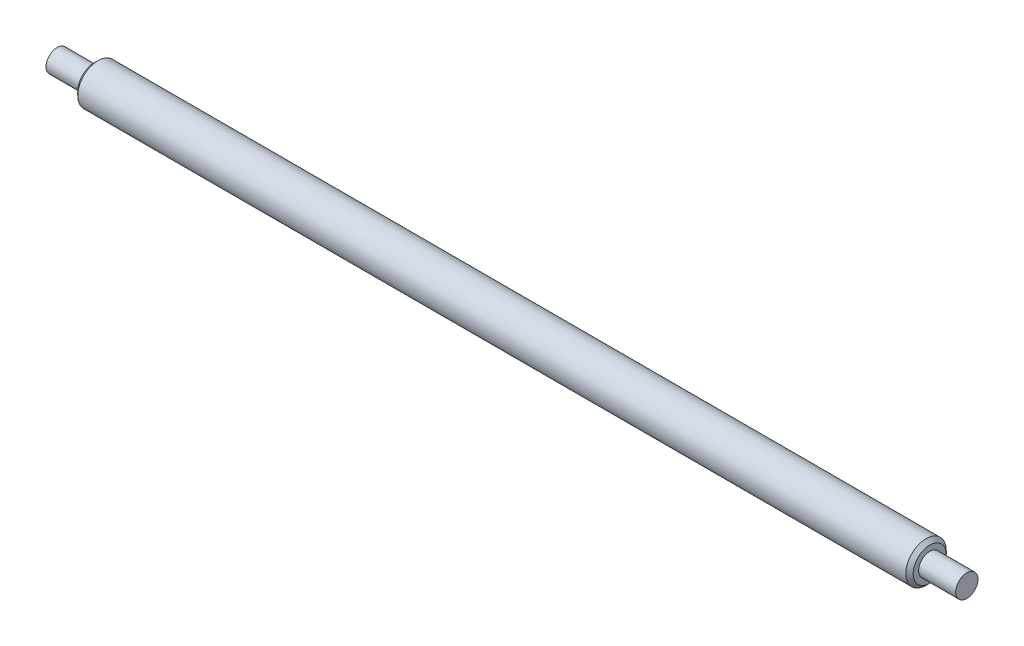
SolidWorks part; units mm, degrees
ref_plane "Front Plane" through (0, 0, 0) normal (0, 0, 1) x (1, 0, 0)
ref_plane "Top Plane" through (0, 0, 0) normal (0, 1, 0) x (1, 0, 0)
ref_plane "Right Plane" through (0, 0, 0) normal (1, 0, 0) x (0, 0, -1)
sketch "Sketch1" plane through (0, 0, 0) normal (1, 0, 0) x (0, 0, -1)
  circle A0 centre (0, 0) radius 10.9
  dimension "D1" = 21.8
extrude "Boss-Extrude1" add sketch "Sketch1" along normal mid plane 490
sketch "Sketch2" plane through (245, 0, 0) normal (1, 0, 0) x (0, 0, -1)
  circle A1 centre (0, 0) radius 6
  circle A2 centre (0, 0) radius 10.9
  circle A3 centre (0, 0) radius 10.9
  dimension "D2" = 12
  dimension "D1" = 0
extrude "Cut-Extrude1" cut sketch "Sketch2" against normal blind 20
ref_plane "Plane1" through (-10, 0, 0) normal (-1, 0, 0) x (0, 0, 1)
sketch "Sketch4" plane through (-245, 0, 0) normal (-1, 0, 0) x (0, 0, 1)
  circle A0 centre (0, 0) radius 10.9
  circle A1 centre (0, 0) radius 6
  dimension "D1" = 12
extrude "Cut-Extrude2" cut sketch "Sketch4" against normal blind 20
chamfer "Chamfer1" distance 2 angle 45 2 edges at (-225, 0, 10.9) (225, 0, -10.9)
